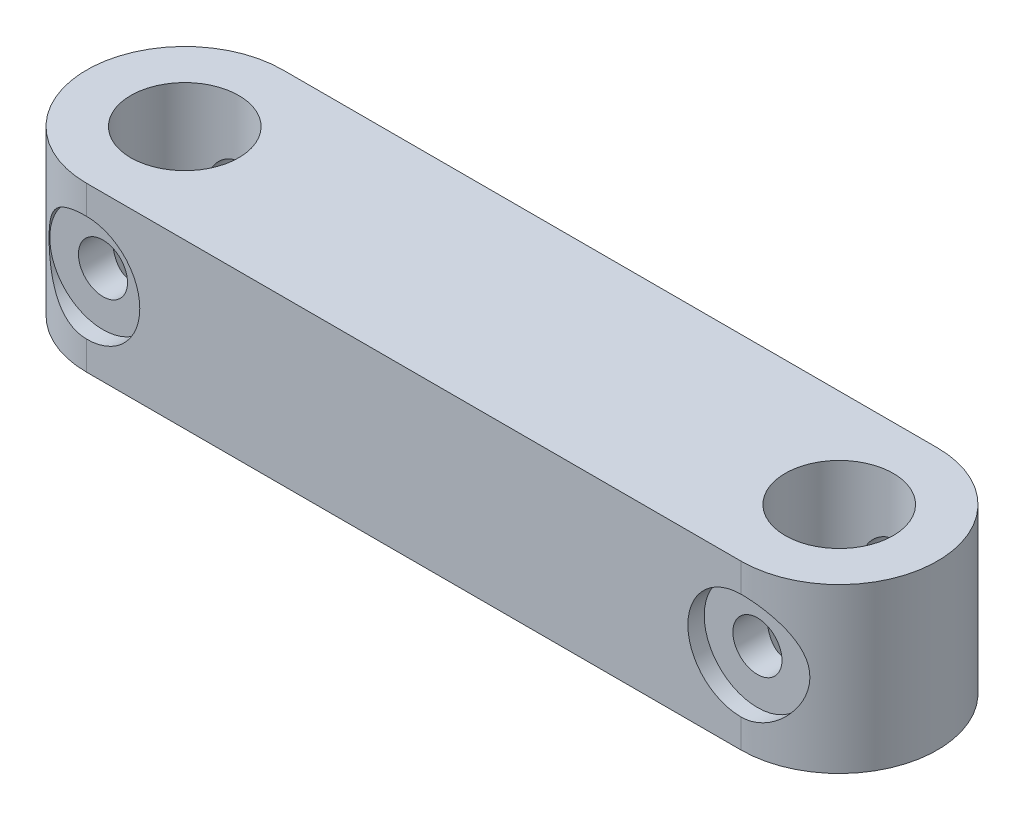
SolidWorks part; units mm, degrees
ref_plane "Alzado" through (0, 0, 0) normal (0, 0, 1) x (1, 0, 0)
ref_plane "Planta" through (0, 0, 0) normal (0, 1, 0) x (1, 0, 0)
ref_plane "Vista lateral" through (0, 0, 0) normal (1, 0, 0) x (0, 0, -1)
sketch "Croquis1" plane through (0, 0, 0) normal (0, 1, 0) x (1, 0, 0)
  line L0 (-20, 6) -> (20, 6)
  line L1 (0, -55) -> (0, 55) construction
  line L2 (20, -6) -> (-20, -6)
  line L3 (-55, 0) -> (55, 0) construction
  arc A0 (20, 6) -> (20, -6) centre (20, 0) cw
  arc A1 (-20, 6) -> (-20, -6) centre (-20, 0) ccw
  point P0 (-26, 0)
  point P7 (0, 6)
  point P10 (0, -6)
  dimension "D1" = 40
  dimension "D2" = 6
extrude "Saliente-Extruir1" add sketch "Croquis1" along normal blind 10
sketch "Croquis2" plane through (0, 0, 0) normal (0, 1, 0) x (1, 0, 0)
  line L0 (-5.5, 0) -> (5.5, 0) construction
  circle A0 centre (-20, 0) radius 3.3
  circle A1 centre (20, 0) radius 3.3
  arc A2 (-20, 6) -> (-20, -6) centre (-20, 0) ccw construction
  arc A3 (20, -6) -> (20, 6) centre (20, 0) ccw construction
  dimension "D1" = 6.6
extrude "Cortar-Extruir1" cut sketch "Croquis2" along normal through all
sketch "Croquis3" plane through (0, 0, 0) normal (0, 0, 1) x (1, 0, 0)
  line L0 (-20, 10) -> (-20, 0) construction
  line L1 (0, -5.5) -> (0, 5.5) construction
  circle A0 centre (-20, 5) radius 1.5
  circle A1 centre (20, 5) radius 1.5
  dimension "D1" = 3
extrude "Cortar-Extruir2" cut sketch "Croquis3" against normal through all both and the other way through all
sketch "Croquis4" plane through (0, 0, 6) normal (0, 0, 1) x (1, 0, 0)
  line L0 (0, -5.5) -> (0, 5.5) construction
  circle A0 centre (-20, 5) radius 3.25
  circle A1 centre (20, 5) radius 3.25
  dimension "D1" = 6.5
extrude "Cortar-Extruir3" cut sketch "Croquis4" against normal blind 1
